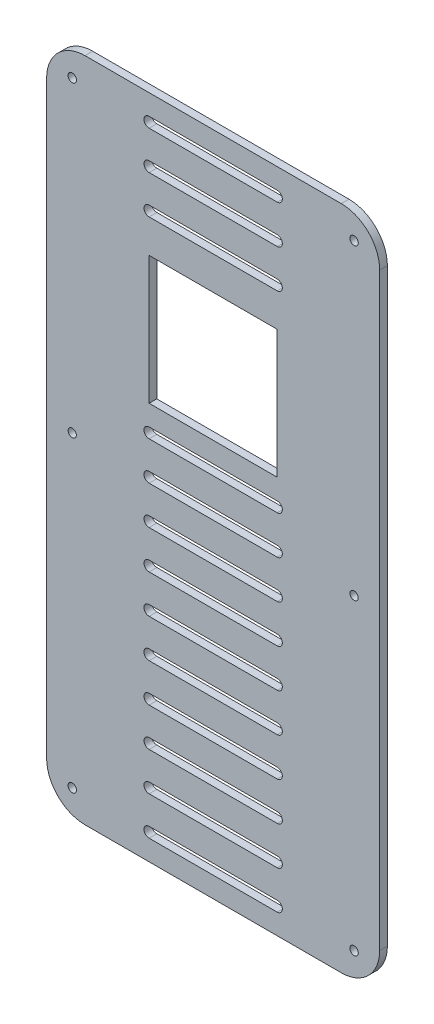
SolidWorks part; units mm, degrees
material "Thornel Mat VMA"
ref_plane "前视基准面" through (0, 0, 0) normal (0, 0, 1) x (1, 0, 0)
ref_plane "上视基准面" through (0, 0, 0) normal (0, 1, 0) x (1, 0, 0)
ref_plane "右视基准面" through (0, 0, 0) normal (1, 0, 0) x (0, 0, -1)
sketch "草图1" plane through (0, 0, 0) normal (0, 0, 1) x (1, 0, 0)
  line L1 (0, 0) -> (130, 0)
  line L2 (0, 0) -> (0, 260)
  line L3 (0, 260) -> (130, 260)
  line L4 (130, 0) -> (130, 260)
  dimension "D1" = 260
  dimension "D2" = 130
extrude "凸台-拉伸1" add sketch "草图1" along normal blind 3 contours L3 L4 L1 L2
sketch "草图2" plane through (0, 0, 3) normal (0, 0, 1) x (1, 0, 0)
  line L0 (0, 0) -> (174.0174, 0) construction
  line L1 (0, 15.9013) -> (0, 0) construction
  line L3 (0, 10) -> (130, 10) construction
  line L4 (130, 0) -> (130, 260) construction
  line L5 (65, 0) -> (65, 260) construction
  line L6 (0, 260) -> (130, 260) construction
  line L7 (0, 130) -> (130, 130) construction
  circle A0 centre (120, 10) radius 1.65
  circle A1 centre (10, 10) radius 1.65
  circle A2 centre (10, 250) radius 1.65
  circle A3 centre (120, 250) radius 1.65
  circle A4 centre (120, 130) radius 1.6
  circle A5 centre (10, 130) radius 1.605
  dimension "D5" = 3.3
  dimension "D6" = 3.3
  dimension "D8" = 3.2
  dimension "D9" = 3.21
  dimension "D1" = 10
  dimension "D2" = 65
  dimension "D3" = 10
  dimension "D4" = 10
  dimension "D7" = 130
  dimension "D10" = 10
  dimension "D11" = 10
extrude "切除-拉伸1" cut sketch "草图2" against normal blind 3
sketch "草图3" plane through (0, 0, 0) normal (0, 0, -1) x (-1, 0, 0)
  line L1 (-90, 155) -> (-40, 155)
  line L2 (-90, 155) -> (-90, 205)
  line L3 (-90, 205) -> (-40, 205)
  line L4 (-40, 155) -> (-40, 205)
  line L6 (-65, 260) -> (-65, 0) construction
  line L7 (0, 260) -> (-130, 260) construction
  line L8 (0, 0) -> (-130, 0) construction
  line L9 (-130, 180) -> (0, 180) construction
  line L10 (-130, 0) -> (-130, 260) construction
  line L11 (0, 0) -> (0, 260) construction
  dimension "D1" = 80
  dimension "D2" = 25
  dimension "D3" = 25
  dimension "D4" = 25
  dimension "D5" = 25
extrude "切除-拉伸2" cut sketch "草图3" against normal blind 10
fillet "圆角1" radius 15 4 edges at (0, 260, 1.5) (0, 0, 1.5) (130, 0, 1.5) (130, 260, 1.5)
sketch "草图4" plane through (0, 0, 0) normal (0, 0, -1) x (-1, 0, 0)
  line L0 (-65, 0) -> (-65, 260) construction
  line L1 (-15, 0) -> (-115, 0) construction
  line L2 (-15, 260) -> (-115, 260) construction
  line L3 (-90, 10) -> (-40, 10) construction
  line L4 (-90, 12) -> (-40, 12)
  line L5 (-90, 8) -> (-40, 8)
  line L6 (-90, 25) -> (-40, 25) construction
  line L7 (-90, 27) -> (-40, 27)
  line L8 (-90, 23) -> (-40, 23)
  line L9 (-90, 40) -> (-40, 40) construction
  line L10 (-90, 42) -> (-40, 42)
  line L11 (-90, 38) -> (-40, 38)
  line L12 (-90, 55) -> (-40, 55) construction
  line L13 (-90, 57) -> (-40, 57)
  line L14 (-90, 53) -> (-40, 53)
  line L15 (-90, 70) -> (-40, 70) construction
  line L16 (-90, 72) -> (-40, 72)
  line L17 (-90, 68) -> (-40, 68)
  line L18 (-90, 85) -> (-40, 85) construction
  line L19 (-90, 87) -> (-40, 87)
  line L20 (-90, 83) -> (-40, 83)
  line L21 (-90, 100) -> (-40, 100) construction
  line L22 (-90, 102) -> (-40, 102)
  line L23 (-90, 98) -> (-40, 98)
  line L24 (-90, 115) -> (-40, 115) construction
  line L25 (-90, 117) -> (-40, 117)
  line L26 (-90, 113) -> (-40, 113)
  line L27 (-90, 130) -> (-40, 130) construction
  line L28 (-90, 132) -> (-40, 132)
  line L29 (-90, 128) -> (-40, 128)
  line L30 (-90, 145) -> (-40, 145) construction
  line L31 (-90, 147) -> (-40, 147)
  line L32 (-90, 143) -> (-40, 143)
  line L45 (-90, 220) -> (-40, 220) construction
  line L46 (-90, 222) -> (-40, 222)
  line L47 (-90, 218) -> (-40, 218)
  line L48 (-90, 235) -> (-40, 235) construction
  line L49 (-90, 237) -> (-40, 237)
  line L50 (-90, 233) -> (-40, 233)
  line L51 (-90, 250) -> (-40, 250) construction
  line L52 (-90, 252) -> (-40, 252)
  line L53 (-90, 248) -> (-40, 248)
  line L54 (-90, 160) -> (-40, 160) construction
  line L55 (-90, 162) -> (-40, 162)
  line L56 (-90, 158) -> (-40, 158)
  line L57 (-90, 175) -> (-40, 175) construction
  line L58 (-90, 177) -> (-40, 177)
  line L59 (-90, 173) -> (-40, 173)
  line L60 (-90, 190) -> (-40, 190) construction
  line L61 (-90, 192) -> (-40, 192)
  line L62 (-90, 188) -> (-40, 188)
  line L63 (-90, 205) -> (-40, 205) construction
  line L64 (-90, 207) -> (-40, 207)
  line L65 (-90, 203) -> (-40, 203)
  line L66 (-90, 160) -> (-40, 160) construction
  line L67 (-90, 162) -> (-40, 162)
  line L68 (-90, 158) -> (-40, 158)
  line L69 (-90, 175) -> (-40, 175) construction
  line L70 (-90, 177) -> (-40, 177)
  line L71 (-90, 173) -> (-40, 173)
  line L72 (-90, 190) -> (-40, 190) construction
  line L73 (-90, 192) -> (-40, 192)
  line L74 (-90, 188) -> (-40, 188)
  line L75 (-90, 205) -> (-40, 205) construction
  line L76 (-90, 207) -> (-40, 207)
  line L77 (-90, 203) -> (-40, 203)
  arc A0 (-90, 12) -> (-90, 8) centre (-90, 10) ccw
  arc A1 (-40, 8) -> (-40, 12) centre (-40, 10) ccw
  arc A2 (-90, 27) -> (-90, 23) centre (-90, 25) ccw
  arc A3 (-40, 23) -> (-40, 27) centre (-40, 25) ccw
  arc A4 (-90, 42) -> (-90, 38) centre (-90, 40) ccw
  arc A5 (-40, 38) -> (-40, 42) centre (-40, 40) ccw
  arc A6 (-90, 57) -> (-90, 53) centre (-90, 55) ccw
  arc A7 (-40, 53) -> (-40, 57) centre (-40, 55) ccw
  arc A8 (-90, 72) -> (-90, 68) centre (-90, 70) ccw
  arc A9 (-40, 68) -> (-40, 72) centre (-40, 70) ccw
  arc A10 (-90, 87) -> (-90, 83) centre (-90, 85) ccw
  arc A11 (-40, 83) -> (-40, 87) centre (-40, 85) ccw
  arc A12 (-90, 102) -> (-90, 98) centre (-90, 100) ccw
  arc A13 (-40, 98) -> (-40, 102) centre (-40, 100) ccw
  arc A14 (-90, 117) -> (-90, 113) centre (-90, 115) ccw
  arc A15 (-40, 113) -> (-40, 117) centre (-40, 115) ccw
  arc A16 (-90, 132) -> (-90, 128) centre (-90, 130) ccw
  arc A17 (-40, 128) -> (-40, 132) centre (-40, 130) ccw
  arc A18 (-90, 147) -> (-90, 143) centre (-90, 145) ccw
  arc A19 (-40, 143) -> (-40, 147) centre (-40, 145) ccw
  arc A28 (-90, 222) -> (-90, 218) centre (-90, 220) ccw
  arc A29 (-40, 218) -> (-40, 222) centre (-40, 220) ccw
  arc A30 (-90, 237) -> (-90, 233) centre (-90, 235) ccw
  arc A31 (-40, 233) -> (-40, 237) centre (-40, 235) ccw
  arc A32 (-90, 252) -> (-90, 248) centre (-90, 250) ccw
  arc A33 (-40, 248) -> (-40, 252) centre (-40, 250) ccw
  arc A42 (-90, 162) -> (-90, 158) centre (-90, 160) ccw
  arc A43 (-40, 158) -> (-40, 162) centre (-40, 160) ccw
  arc A44 (-90, 177) -> (-90, 173) centre (-90, 175) ccw
  arc A45 (-40, 173) -> (-40, 177) centre (-40, 175) ccw
  arc A46 (-90, 192) -> (-90, 188) centre (-90, 190) ccw
  arc A47 (-40, 188) -> (-40, 192) centre (-40, 190) ccw
  arc A48 (-90, 207) -> (-90, 203) centre (-90, 205) ccw
  arc A49 (-40, 203) -> (-40, 207) centre (-40, 205) ccw
  point P8 (-65, 10)
  point P17 (-65, 25)
  point P24 (-65, 40)
  point P31 (-65, 55)
  point P38 (-65, 70)
  point P45 (-65, 85)
  point P52 (-65, 100)
  point P59 (-65, 115)
  point P66 (-65, 130)
  point P73 (-65, 145)
  point P80 (-65, 160)
  point P87 (-65, 175)
  point P94 (-65, 190)
  point P101 (-65, 205)
  point P108 (-65, 220)
  point P115 (-65, 235)
  point P122 (-65, 250)
  point P129 (-65, 160)
  point P136 (-65, 175)
  point P143 (-65, 190)
  point P150 (-65, 205)
  point P157 (-65, 160)
  point P164 (-65, 175)
  point P171 (-65, 190)
  point P178 (-65, 205)
  dimension "D1" = 10
  dimension "D2" = 4
  dimension "D3" = 50
  dimension "D5" = 15
  dimension "D4" = 17
extrude "切除-拉伸4" cut sketch "草图4" against normal blind 10
